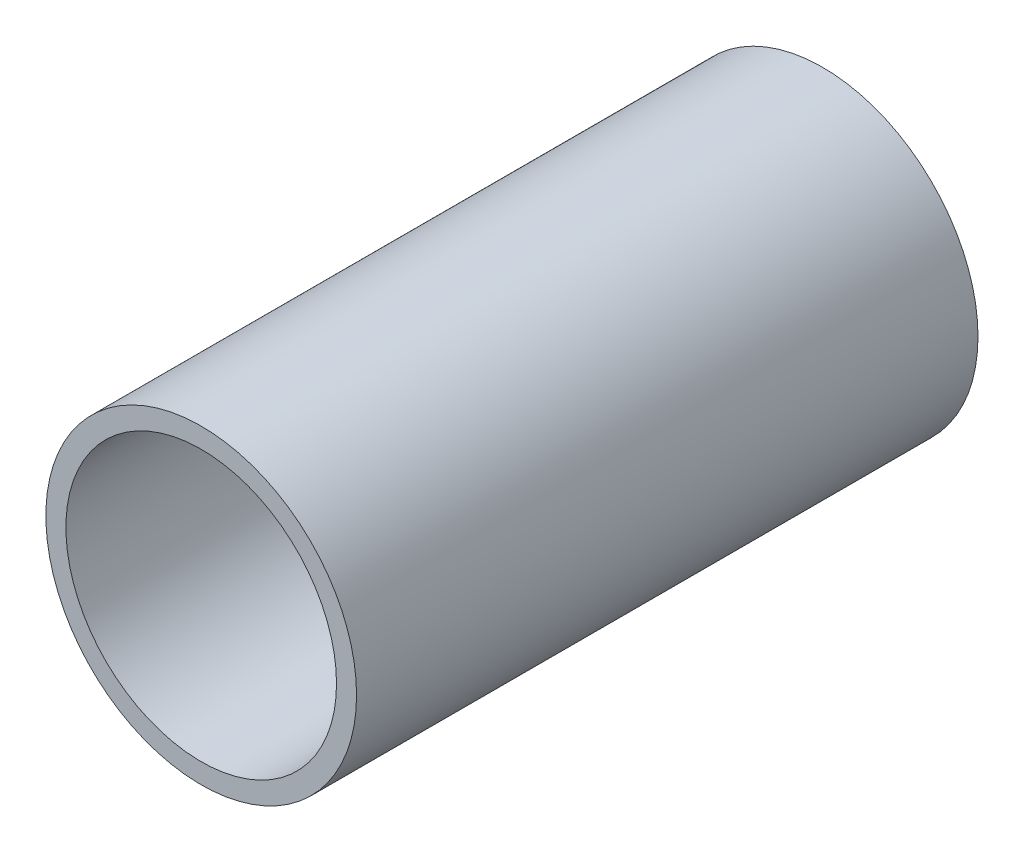
SolidWorks part; units mm, degrees
ref_plane "前视基准面" through (0, 0, 0) normal (0, 0, 1) x (1, 0, 0)
ref_plane "上视基准面" through (0, 0, 0) normal (0, 1, 0) x (1, 0, 0)
ref_plane "右视基准面" through (0, 0, 0) normal (1, 0, 0) x (0, 0, -1)
other "Configuration Table"
sketch "草图1" plane through (0, 0, 0) normal (0, 0, 1) x (1, 0, 0)
  circle A0 centre (0, 0) radius 6.75
  circle A1 centre (0, 0) radius 7.75
  dimension "D1" = 15.5
  dimension "D2" = 1
extrude "凸台-拉伸1" add sketch "草图1" along normal blind 31
